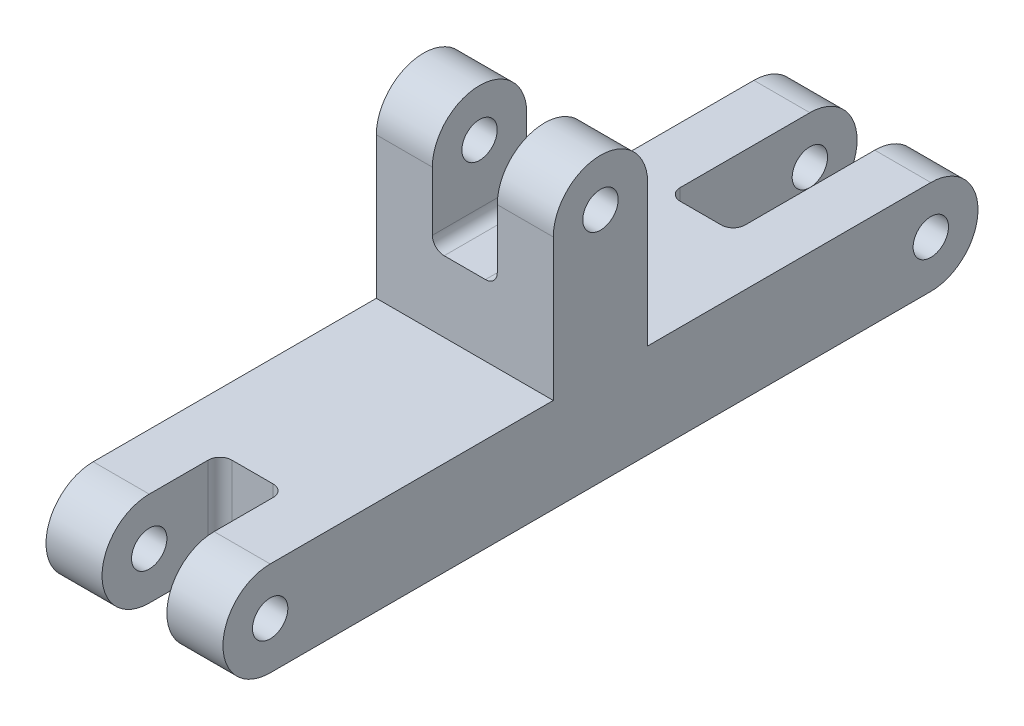
SolidWorks part; units mm, degrees
ref_plane "Alzado" through (0, 0, 0) normal (0, 0, 1) x (1, 0, 0)
ref_plane "Planta" through (0, 0, 0) normal (0, 1, 0) x (1, 0, 0)
ref_plane "Vista lateral" through (0, 0, 0) normal (1, 0, 0) x (0, 0, -1)
sketch "Croquis1" plane through (0, 0, 0) normal (1, 0, 0) x (0, 0, -1)
  line L0 (-15, 0) -> (15, 0) construction
  line L1 (-15, 4) -> (-17, 4) construction
  line L2 (-15, -4) -> (15, -4)
  line L3 (-9, 4) -> (15, 4)
  line L5 (-17, 4) -> (-17, 16)
  line L6 (-17, 16) -> (-9, 16) construction
  line L7 (-9, 4) -> (-9, 16)
  line L8 (-17, 4) -> (-41, 4)
  line L9 (-15, -4) -> (-41, -4)
  line L10 (-41, 4) -> (-41, -4) construction
  arc A0 (-15, 4) -> (-15, -4) centre (-15, 0) ccw construction
  arc A1 (15, -4) -> (15, 4) centre (15, 0) ccw
  circle A2 centre (15, 0) radius 1.5
  arc A3 (-9, 16) -> (-17, 16) centre (-13, 16) ccw
  circle A4 centre (-13, 16) radius 1.5
  circle A5 centre (-15, 0) radius 1.5 construction
  arc A6 (-41, 4) -> (-41, -4) centre (-41, 0) ccw
  circle A7 centre (-41, 0) radius 1.5
  point P3 (0, 0)
  dimension "D2" = 4
  dimension "D3" = 3
  dimension "D4" = 4
  dimension "D7" = 24
  dimension "D1" = 30
  dimension "D5" = 24
  dimension "D6" = 12
extrude "Saliente-Extruir1" add sketch "Croquis1" along normal mid plane 15
sketch "Croquis2" plane through (0, 0, 0) normal (1, 0, 0) x (0, 0, -1)
  line L0 (-17, 16) -> (-17, 4) construction
  line L1 (-17, 10) -> (-9, 10)
  line L2 (-17, 10) -> (-17, 20)
  line L3 (-17, 20) -> (-9, 20)
  line L4 (-9, 10) -> (-9, 20)
  line L5 (-9, 4) -> (-9, 16) construction
  line L11 (-41, -4) -> (15, -4) construction
  line L12 (15, 4) -> (-9, 4) construction
  line L13 (3, 4) -> (19, 4)
  line L14 (3, 4) -> (3, -4)
  line L15 (3, -4) -> (19, -4)
  line L16 (19, 4) -> (19, -4)
  line L18 (-35, 4) -> (-45, 4)
  line L19 (-35, 4) -> (-35, -4)
  line L20 (-35, -4) -> (-45, -4)
  line L21 (-45, 4) -> (-45, -4)
  line L22 (-41, -4) -> (15, -4) construction
  line L23 (-17, 4) -> (-41, 4) construction
  arc A0 (-9, 16) -> (-17, 16) centre (-13, 16) ccw construction
  arc A2 (15, -4) -> (15, 4) centre (15, 0) ccw construction
  arc A5 (-41, 4) -> (-41, -4) centre (-41, 0) ccw construction
  dimension "D5" = 10
  dimension "D1" = 10
  dimension "D3" = 16
extrude "Cortar-Extruir1" cut sketch "Croquis2" against normal mid plane 5.5
fillet "Redondeo1" radius 1 6 edges at (2.75, 0, 35) (-2.75, 0, 35) (2.75, 0, -3) (-2.75, 0, -3) (2.75, 10, 13) (-2.75, 10, 13)
